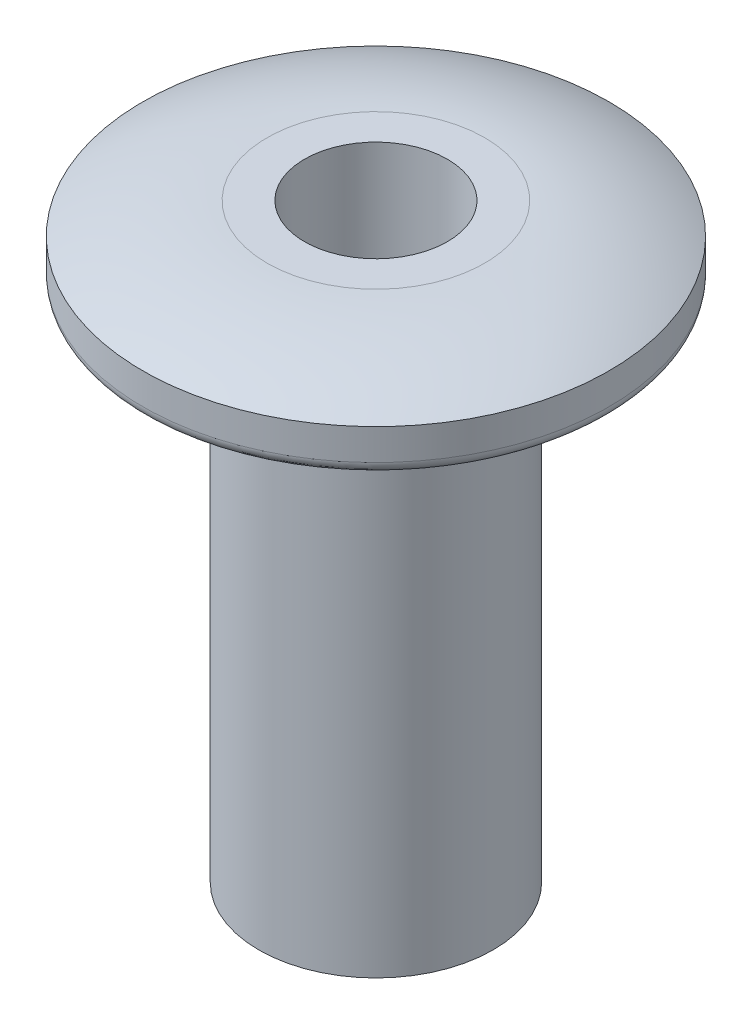
SolidWorks part; units mm, degrees
material "AISI 1010 Steel, hot rolled bar"
ref_plane "Front Plane" through (0, 0, 0) normal (0, 0, 1) x (1, 0, 0)
ref_plane "Top Plane" through (0, 0, 0) normal (0, 1, 0) x (1, 0, 0)
ref_plane "Right Plane" through (0, 0, 0) normal (1, 0, 0) x (0, 0, -1)
sketch "Sketch1" plane through (0, 0, 0) normal (0, 0, 1) x (1, 0, 0)
  line L0 (0, 0) -> (0, 26.8035) construction
  line L1 (-1.4605, 0) -> (-1.4605, 12.065)
  line L2 (-1.4605, 12.065) -> (-2.2225, 12.065)
  line L4 (-4.7625, 11.43) -> (-4.7625, 10.795)
  line L5 (-4.5085, 10.541) -> (-2.394, 10.541)
  line L6 (-2.394, 10.541) -> (-2.3939, 0)
  line L7 (-2.3939, 0) -> (-1.4605, 0)
  arc A0 (-4.7625, 10.795) -> (-4.5085, 10.541) centre (-4.5085, 10.795) ccw
  arc A1 (-2.2225, 12.065) -> (-4.7625, 11.43) centre (-2.2225, 6.6675) ccw
  dimension "D7" = 0.254
  dimension "D1" = 1.524
  dimension "D2" = 0.635
  dimension "D3" = 9.525
  dimension "D4" = 0.9335
  dimension "D5" = 2.921
  dimension "D6" = 2.54
  dimension "D8" = 12.065
revolve "Revolve1" add sketch "Sketch1" angle 360 about L0
fillet "Fillet1" [suppressed] radius 0.508
